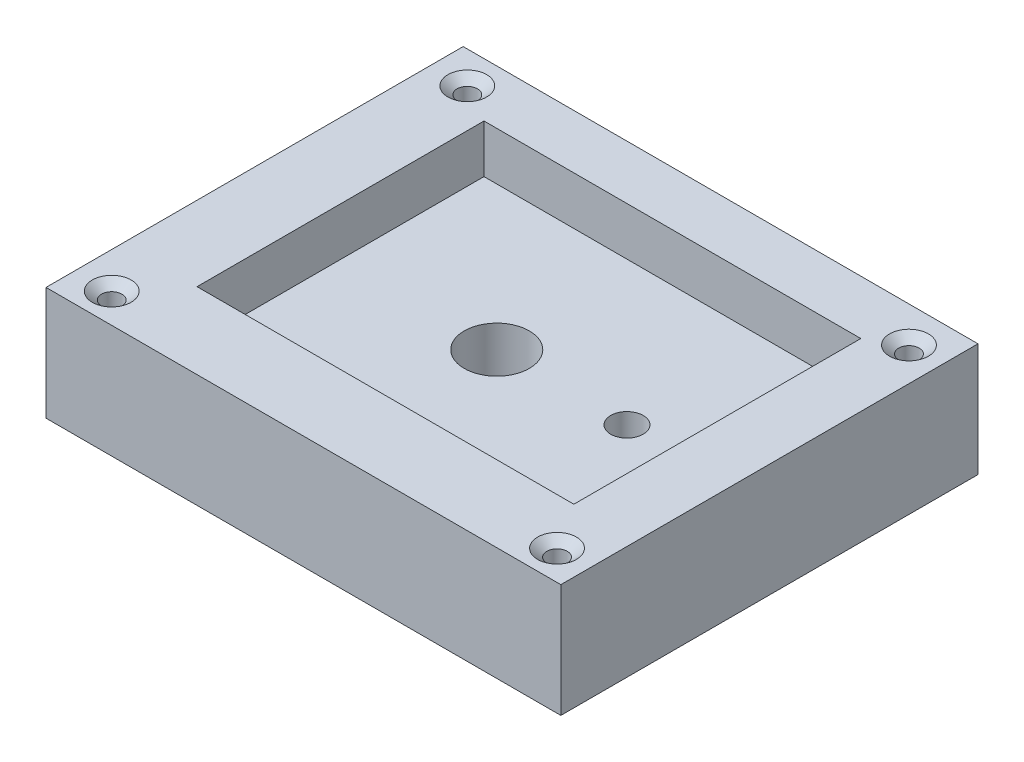
SolidWorks part; units mm, degrees
ref_plane "Front Plane" through (0, 0, 0) normal (0, 0, 1) x (1, 0, 0)
ref_plane "Top Plane" through (0, 0, 0) normal (0, 1, 0) x (1, 0, 0)
ref_plane "Right Plane" through (0, 0, 0) normal (1, 0, 0) x (0, 0, -1)
sketch "Sketch1" plane through (0, 0, 0) normal (0, 1, 0) x (1, 0, 0)
  line L1 (0, 0) -> (-50.2158, 0)
  line L2 (0, 0) -> (0, 40.6908)
  line L3 (0, 40.6908) -> (-50.2158, 40.6908)
  line L4 (-50.2158, 0) -> (-50.2158, 40.6908)
  dimension "D1" = 40.6908
  dimension "D2" = 50.2158
extrude "Boss-Extrude1" add sketch "Sketch1" along normal blind 11.049
sketch "Sketch2" plane through (0, 11.049, 0) normal (0, 1, 0) x (1, 0, 0)
  line L1 (-6.1585, 7.4284) -> (-42.9123, 7.4284)
  line L2 (-6.1585, 7.4284) -> (-6.1585, 35.4192)
  line L3 (-6.1585, 35.4192) -> (-42.9123, 35.4192)
  line L4 (-42.9123, 7.4284) -> (-42.9123, 35.4192)
  line L5 (-6.1585, 7.4284) -> (-42.9123, 35.4192) construction
  line L6 (-6.1585, 35.4192) -> (-42.9123, 7.4284) construction
  point P0 (-24.5354, 21.4238)
  dimension "D1" = 36.7538
  dimension "D2" = 27.9908
extrude "Cut-Extrude1" cut sketch "Sketch2" against normal blind 4.699 contours L1 L4 L3 L2
sketch "Sketch3" plane through (0, 6.35, 0) normal (0, 1, 0) x (1, 0, 0)
  line L0 (-42.9123, 7.4284) -> (-42.9123, 35.4192) construction
  circle A0 centre (-27.6723, 21.4238) radius 3.175
  circle A1 centre (-14.9723, 21.4238) radius 1.5875
  dimension "D1" = 6.35
  dimension "D2" = 3.175
  dimension "D3" = 15.24
  dimension "D4" = 12.7
extrude "Cut-Extrude2" cut sketch "Sketch3" against normal through all
sketch "Sketch4" plane through (0, 11.049, 0) normal (0, 1, 0) x (1, 0, 0)
  circle A0 centre (-46.6966, 37.5742) radius 1.2954
  circle A1 centre (-3.2599, 37.2177) radius 0.5043
  circle A2 centre (-46.6966, 2.8897) radius 0.4862
  circle A3 centre (-3.2599, 2.8897) radius 0.5186
  point P0 (-46.6966, 37.5742)
  point P2 (-3.2599, 37.2177)
  point P4 (-46.6966, 2.8897)
  point P6 (-3.2599, 2.8897)
hole_wizard "#3-48 Tapped Hole1" positions "Sketch4" profile "Sketch5" tap size "#3-48" standard "ANSI Inch" end condition through all
sketch "Sketch5" plane through (-46.6966, 11.049, -37.5742) normal (1, 0, 0) x (0, 0, 1)
  line L0 (0, 0) -> (0, 11.049)
  line L1 (0, 11.049) -> (0.9969, 11.049)
  line L2 (0.9969, 11.049) -> (0.9969, 0.7513)
  line L3 (0.9969, 0.7513) -> (1.8923, 0)
  line L5 (1.8923, 0) -> (0, 0)
  line L6 (-0.9969, 0.7513) -> (-1.8923, 0) construction
  line L11 (0, -6.35) -> (0, 107.95) construction
  dimension "Thru Tap Drill Dia." = 1.9939
  dimension "Thru Tap Drill Depth" = 11.049
  dimension "Near C'Sink Dia." = 3.7846
  dimension "Near C'Sink Angle" = 100
cosmetic thread "Hole Thread1" parameters "D2"=2.5146
cosmetic thread "Hole Thread2" parameters "D2"=2.5146
cosmetic thread "Hole Thread3" parameters "D2"=2.5146
cosmetic thread "Hole Thread4" parameters "D2"=2.5146
